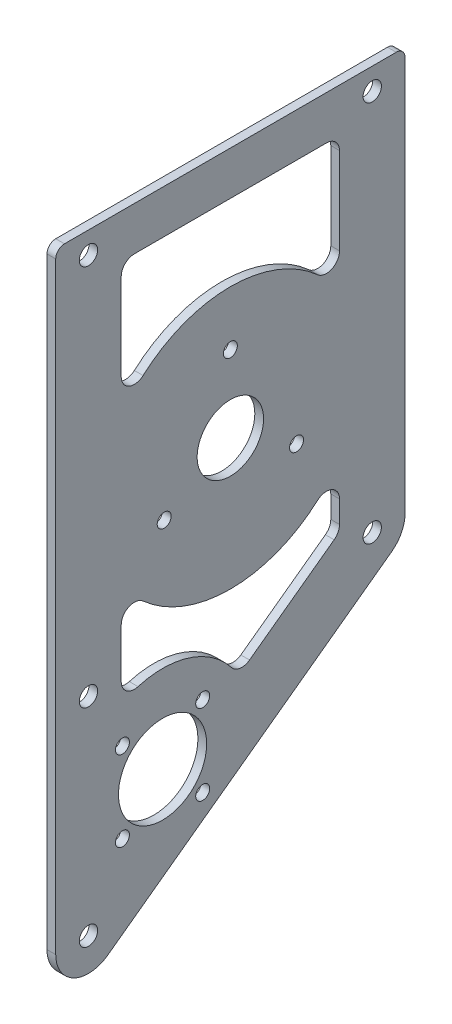
SolidWorks part; units mm, degrees
material "5052-H34"
ref_plane "正面" through (0, 0, 0) normal (0, 0, 1) x (1, 0, 0)
ref_plane "平面" through (0, 0, 0) normal (0, 1, 0) x (1, 0, 0)
ref_plane "右側面" through (0, 0, 0) normal (1, 0, 0) x (0, 0, -1)
sketch "ｽｹｯﾁ1" plane through (0, 0, 0) normal (1, 0, 0) x (0, 0, -1)
  line L0 (0, 0) -> (0, 52.5) construction
  line L1 (0, 52.5) -> (-32.5, 52.5) construction
  line L2 (-32.5, 47.5) -> (-32.5, -93.6959) construction
  line L3 (0, 0) -> (-15.5291, -57.9555) construction
  line L4 (32.5, 52.5) -> (32.5, -35) construction
  line L5 (-24.7215, -48.7632) -> (-6.3368, -48.7632) construction
  line L6 (-24.7215, -48.7632) -> (-24.7215, -67.1479) construction
  line L7 (-24.7215, -67.1479) -> (-6.3368, -67.1479) construction
  line L8 (-6.3368, -48.7632) -> (-6.3368, -67.1479) construction
  line L9 (-24.7215, -48.7632) -> (-6.3368, -67.1479) construction
  line L10 (-24.7215, -67.1479) -> (-6.3368, -48.7632) construction
  line L11 (0, 0) -> (0, -107.0937) construction
  line L12 (36.9251, -41.0554) -> (-28.0749, -88.5554)
  line L13 (-40, 57.5) -> (40, 57.5)
  line L14 (-40, 57.5) -> (-40, -90)
  line L15 (-40, -90) -> (40, -90)
  line L16 (40, 57.5) -> (40, -90)
  line L17 (-40, 57.5) -> (40, -90) construction
  line L18 (-40, -90) -> (40, 57.5) construction
  circle A0 centre (0, 0) radius 40 construction
  circle A1 centre (-15.5291, -57.9555) radius 20 construction
  circle A2 centre (0, 0) radius 7.6
  circle A3 centre (-32.5, 52.5) radius 2.1
  circle A4 centre (32.5, 52.5) radius 2.1
  circle A5 centre (-15.5291, -57.9555) radius 10.1
  circle A6 centre (-6.3368, -48.7632) radius 1.6
  circle A7 centre (-6.3368, -67.1479) radius 1.6
  circle A8 centre (-24.7215, -67.1479) radius 1.6
  circle A9 centre (-24.7215, -48.7632) radius 1.6
  circle A10 centre (32.5, -35) radius 2.1
  circle A11 centre (-32.5, -82.5) radius 2.1
  circle A14 centre (32.5, -35) radius 7.5
  circle A15 centre (-32.5, -82.5) radius 7.5
  arc A19 (-32.5, -53.6847) -> (-32.5, -62.2264) centre (-15.5291, -57.9555) ccw construction
  arc A20 (-13.212, -40.6096) -> (-32.5, -53.6847) centre (-15.5291, -57.9555) ccw construction
  arc A21 (-10.9998, -41.0518) -> (-13.212, -40.6096) centre (-15.5291, -57.9555) ccw construction
  arc A22 (0, -49.8874) -> (-10.9998, -41.0518) centre (-15.5291, -57.9555) ccw construction
  arc A27 (-32.5, -62.2264) -> (-28.8044, -69.3581) centre (-15.5291, -57.9555) ccw construction
  circle A28 centre (0, 0) radius 17.5 construction
  circle A29 centre (0, 17.5) radius 1.6
  circle A30 centre (15.1554, -8.75) radius 1.6
  circle A31 centre (-15.1554, -8.75) radius 1.6
  circle A32 centre (-32.5, -35) radius 2.1
  point P28 (0, -16.25)
  dimension "D1" = 80
  dimension "D2" = 40
  dimension "D3" = 15.2
  dimension "D4" = 4.2
  dimension "D9" = 20.2
  dimension "D10" = 3.2
  dimension "D17" = 35
  dimension "D18" = 35
  dimension "D19" = 3.2
  dimension "D5" = 65
  dimension "D6" = 52.5
  dimension "D7" = 165
  dimension "D8" = 26
  dimension "D12" = 87.5
  dimension "D13" = 135
  dimension "D14" = 5
  dimension "D15" = 7.5
  dimension "D16" = 7.5
  dimension "D11" = 4
  dimension "D20" = 3
extrude "ﾎﾞｽ - 押し出し1" add sketch "ｽｹｯﾁ1" along normal blind 2
sketch "ｽｹｯﾁ3" plane through (2, 0, 0) normal (1, 0, 0) x (0, 0, -1)
  line L0 (25, 42.5) -> (-25, 42.5)
  line L1 (-25, 42.5) -> (-25, -67.7301)
  line L2 (-25, -67.7301) -> (25, -31.1916)
  line L3 (25, -31.1916) -> (25, 42.5)
  line L4 (-40, 57.5) -> (-40, -82.5)
  line L5 (-28.0749, -88.5554) -> (36.9251, -41.0554)
  line L6 (40, -35) -> (40, 57.5)
  line L7 (40, 57.5) -> (-40, 57.5)
  line L8 (-40, 57.5) -> (-40, -82.5)
  line L9 (-28.0749, -88.5554) -> (36.9251, -41.0554)
  line L10 (40, -35) -> (40, 57.5)
  line L11 (40, 57.5) -> (-40, 57.5)
  line L12 (30, 47.5) -> (-30, 47.5)
  line L13 (-30, 47.5) -> (-30, -77.5767)
  line L14 (-30, -77.5767) -> (30, -33.7305)
  line L15 (30, -33.7305) -> (30, 47.5)
  line L16 (-25, 42.5) -> (-25, 47.5)
  line L17 (25, 42.5) -> (25, 47.5)
  circle A0 centre (0, 0) radius 30
  circle A1 centre (32.5, 52.5) radius 2.1
  arc A2 (-40, -82.5) -> (-28.0749, -88.5554) centre (-32.5, -82.5) ccw
  arc A3 (36.9251, -41.0554) -> (40, -35) centre (32.5, -35) ccw
  arc A4 (-40, -82.5) -> (-28.0749, -88.5554) centre (-32.5, -82.5) ccw
  arc A5 (36.9251, -41.0554) -> (40, -35) centre (32.5, -35) ccw
  circle A6 centre (32.5, 52.5) radius 2.1
  circle A7 centre (-32.5, 52.5) radius 2.1
  circle A8 centre (-32.5, 52.5) radius 2.1
  circle A9 centre (0, 0) radius 7.6
  circle A10 centre (0, 0) radius 7.6
  circle A11 centre (-15.5291, -57.9555) radius 10.1
  circle A12 centre (-15.5291, -57.9555) radius 10.1
  circle A13 centre (-6.3368, -48.7632) radius 1.6
  circle A14 centre (-6.3368, -48.7632) radius 1.6
  circle A15 centre (-6.3368, -67.1479) radius 1.6
  circle A16 centre (-6.3368, -67.1479) radius 1.6
  circle A17 centre (-24.7215, -67.1479) radius 1.6
  circle A18 centre (-24.7215, -67.1479) radius 1.6
  circle A19 centre (-24.7215, -48.7632) radius 1.6
  circle A20 centre (-24.7215, -48.7632) radius 1.6
  circle A21 centre (0, 17.5) radius 1.6
  circle A22 centre (0, 17.5) radius 1.6
  circle A23 centre (15.1554, -8.75) radius 1.6
  circle A24 centre (15.1554, -8.75) radius 1.6
  circle A25 centre (-15.1554, -8.75) radius 1.6
  circle A26 centre (-15.1554, -8.75) radius 1.6
  circle A27 centre (-32.5, -35) radius 2.1
  circle A28 centre (-32.5, -35) radius 2.1
  circle A29 centre (32.5, -35) radius 2.1
  circle A30 centre (32.5, -35) radius 2.1
  circle A31 centre (-32.5, -82.5) radius 2.1
  circle A32 centre (-32.5, -82.5) radius 2.1
  circle A33 centre (-15.5291, -57.9555) radius 20
  arc A34 (-25, -67.7301) -> (-25, -67.7301) centre (-25, -67.7301) ccw
  arc A35 (25, -31.1916) -> (25, -31.1916) centre (25, -31.1916) ccw
  arc A36 (-30, -77.5767) -> (-30, -77.5767) centre (-30, -77.5767) ccw
  arc A37 (30, -33.7305) -> (30, -33.7305) centre (30, -33.7305) ccw
  dimension "D16" = 60
  dimension "D17" = 40
  dimension "D1" = 0
  dimension "D2" = 0
  dimension "D3" = 0
  dimension "D4" = 0
  dimension "D5" = 0
  dimension "D6" = 0
  dimension "D7" = 0
  dimension "D8" = 0
  dimension "D9" = 0
  dimension "D10" = 0
  dimension "D11" = 0
  dimension "D12" = 0
  dimension "D13" = 0
  dimension "D14" = 0
  dimension "D15" = 0
  dimension "D18" = 15
  dimension "D19" = 10
extrude "ｶｯﾄ - 押し出し1" cut sketch "ｽｹｯﾁ3" against normal through all contours A33 L2 L3 A0 L1 | A0 L3 L0 L1 | L0 L17 L12 L16
fillet "ﾌｨﾚｯﾄ1" radius 3.005 8 edges at (1, -40.3401, 25) (1, -48.0939, -1.8705) (1, -31.1916, -25) (1, -16.5831, -25) (1, 16.5831, -25) (1, -16.5831, 25) (1, 47.5, -25) (1, 47.5, 25)
fillet "ﾌｨﾚｯﾄ2" radius 2 2 edges at (1, 57.5, -40) (1, 57.5, 40)
